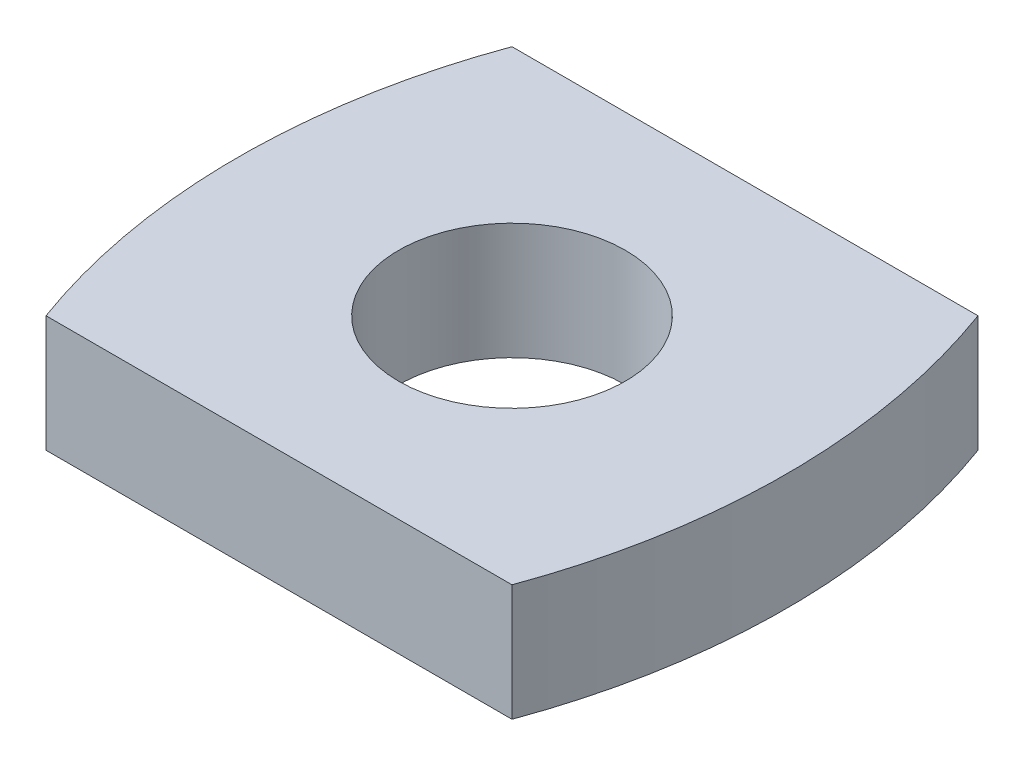
SolidWorks part; units mm, degrees
ref_plane "Front Plane" through (0, 0, 0) normal (0, 0, 1) x (1, 0, 0)
ref_plane "Top Plane" through (0, 0, 0) normal (0, 1, 0) x (1, 0, 0)
ref_plane "Right Plane" through (0, 0, 0) normal (1, 0, 0) x (0, 0, -1)
sketch "Sketch1" plane through (0, 0, 0) normal (0, 1, 0) x (1, 0, 0)
  line L4 (-10, -10) -> (10, -10)
  line L8 (10, 10) -> (-10, 10)
  circle A2 centre (0, 0) radius 4.867
  arc A4 (10, 10) -> (10, -10) centre (-17.3167, 0) cw
  arc A5 (-10, 10) -> (-10, -10) centre (17.3167, 0) ccw
extrude "Boss-Extrude1" add sketch "Sketch1" along normal blind 5
